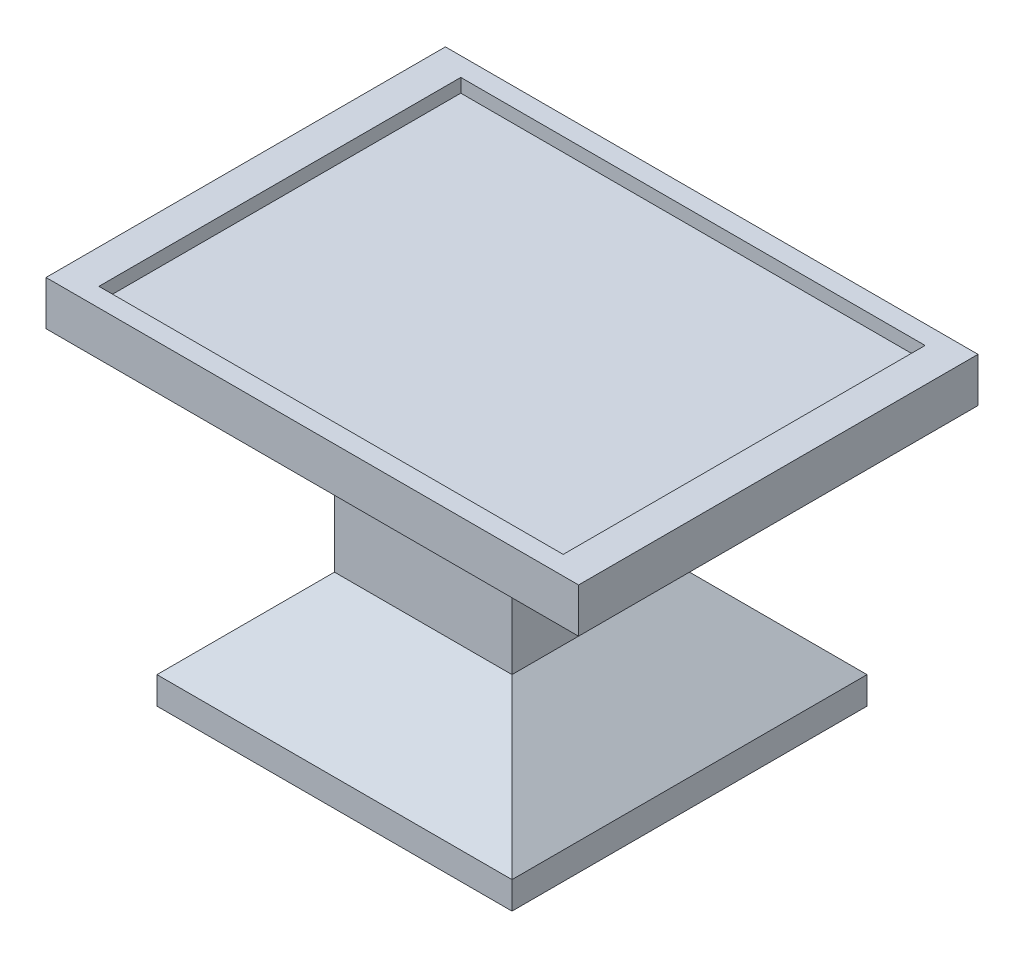
SolidWorks part; units mm, degrees
ref_plane "Front Plane" through (0, 0, 0) normal (0, 0, 1) x (1, 0, 0)
ref_plane "Top Plane" through (0, 0, 0) normal (0, 1, 0) x (1, 0, 0)
ref_plane "Right Plane" through (0, 0, 0) normal (1, 0, 0) x (0, 0, -1)
sketch "Sketch1" plane through (0, 0, 0) normal (0, 1, 0) x (1, 0, 0)
  line L1 (-19.5, 14.625) -> (19.5, 14.625)
  line L2 (-19.5, 14.625) -> (-19.5, -14.625)
  line L3 (-19.5, -14.625) -> (19.5, -14.625)
  line L4 (19.5, 14.625) -> (19.5, -14.625)
  line L5 (-19.5, 14.625) -> (19.5, -14.625) construction
  line L6 (-19.5, -14.625) -> (19.5, 14.625) construction
  point P0 (0, 0)
  dimension "D1" = 39
  dimension "D2" = 29.25
extrude "Boss-Extrude1" add sketch "Sketch1" along normal blind 3.25
sketch "Sketch3" plane through (0, 0, 0) normal (0, -1, 0) x (1, 0, 0)
  line L1 (-6.5, 6.5) -> (6.5, 6.5)
  line L2 (-6.5, 6.5) -> (-6.5, -6.5)
  line L3 (-6.5, -6.5) -> (6.5, -6.5)
  line L4 (6.5, 6.5) -> (6.5, -6.5)
  line L5 (-6.5, 6.5) -> (6.5, -6.5) construction
  line L6 (-6.5, -6.5) -> (6.5, 6.5) construction
  point P0 (0, 0)
  dimension "D1" = 13
  dimension "D2" = 13
extrude "Boss-Extrude3" add sketch "Sketch3" along normal blind 13
ref_plane "Plane1" through (0, -19.5, 0) normal (0, -1, 0) x (-1, 0, 0)
sketch "Sketch4" plane through (0, -19.5, 0) normal (0, -1, 0) x (-1, 0, 0)
  line L1 (-13, 13) -> (13, 13)
  line L2 (-13, 13) -> (-13, -13)
  line L3 (-13, -13) -> (13, -13)
  line L4 (13, 13) -> (13, -13)
  line L5 (-13, 13) -> (13, -13) construction
  line L6 (-13, -13) -> (13, 13) construction
  point P0 (0, 0)
  dimension "D1" = 26
  dimension "D2" = 26
loft "Loft1" add profiles "Sketch4" section "Sketch4" section face at (0, -13, 0)
sketch "Sketch5" plane through (0, 3.25, 0) normal (0, 1, 0) x (1, 0, 0)
  line L1 (-17, 12) -> (17, 12)
  line L2 (-17, 12) -> (-17, -12)
  line L3 (-17, -12) -> (17, -12)
  line L4 (17, 12) -> (17, -12)
  line L5 (-17, 12) -> (17, -12) construction
  line L6 (-17, -12) -> (17, 12) construction
  point P0 (0, 0)
  dimension "D1" = 34
  dimension "D2" = 24
extrude "Cut-Extrude1" cut sketch "Sketch5" against normal blind 1
sketch "Sketch6" plane through (0, -19.5, 0) normal (0, -1, 0) x (1, 0, 0)
  line L1 (-13, 13) -> (13, 13)
  line L2 (-13, 13) -> (-13, -13)
  line L3 (-13, -13) -> (13, -13)
  line L4 (13, 13) -> (13, -13)
  line L5 (-13, 13) -> (13, -13) construction
  line L6 (-13, -13) -> (13, 13) construction
  point P0 (0, 0)
extrude "Boss-Extrude4" add sketch "Sketch6" along normal blind 2
sketch "Sketch8" plane through (0, 3.25, 0) normal (0, 1, 0) x (1, 0, 0)
  line L0 (-17, 12) -> (-17, -12) construction
  line L1 (-17, -13.25) -> (17, -13.25)
  line L2 (-17, -13.25) -> (-17, -12)
  line L3 (-17, -12) -> (17, -12)
  line L4 (17, -13.25) -> (17, -12)
  line L5 (-17, -13.25) -> (17, -12) construction
  line L6 (-17, -12) -> (17, -13.25) construction
  line L14 (-17, -12) -> (17, -12) construction
  point P0 (0, -12.625)
  dimension "D1" = 1.25
extrude "Cut-Extrude2" cut sketch "Sketch8" against normal blind 1
mirror "Mirror1" about plane through (0, 0, 0) normal (0, 0, 1) of "Cut-Extrude2"
